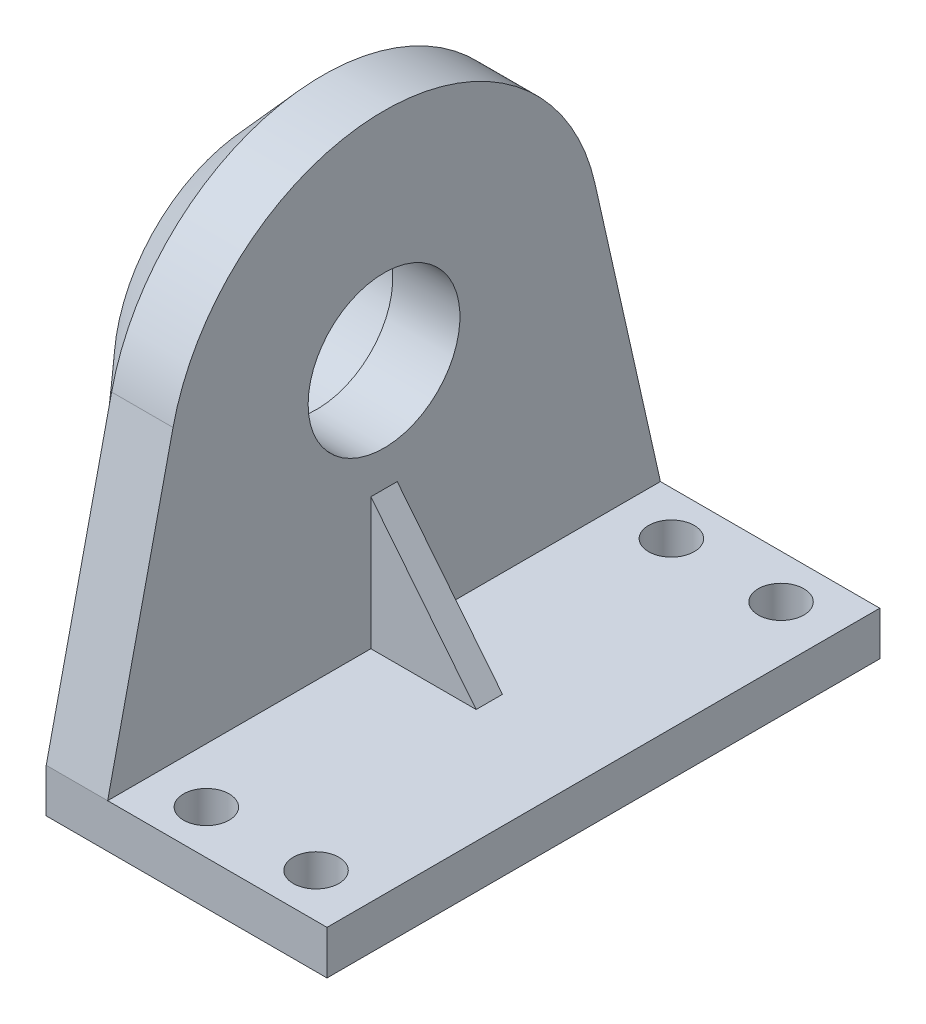
SolidWorks part; units mm, degrees
ref_plane "Front Plane" through (0, 0, 0) normal (0, 0, 1) x (1, 0, 0)
ref_plane "Top Plane" through (0, 0, 0) normal (0, 1, 0) x (1, 0, 0)
ref_plane "Right Plane" through (0, 0, 0) normal (1, 0, 0) x (0, 0, -1)
sketch "Sketch4" plane through (0, 0, 0) normal (0, 0, 1) x (1, 0, 0)
  line L0 (0, 0) -> (22.7302, 0) construction
  line L1 (0, 11.15) -> (7, 11.15)
  line L2 (0, 11.15) -> (0, 16.15)
  line L4 (7, 11.15) -> (7, 8.65)
  line L5 (7, 8.65) -> (14.6534, 8.65)
  line L6 (14.6534, 24.65) -> (14.6534, 8.65)
  line L7 (14.6534, 24.65) -> (7.6534, 24.65)
  line L8 (7.6534, 24.65) -> (0, 16.15)
  dimension "D1" = 11.15
  dimension "D2" = 7
  dimension "D3" = 2.5
  dimension "D4" = 5
  dimension "D5" = 42
  dimension "D6" = 7
  dimension "D7" = 16
revolve "Revolve1" add sketch "Sketch4" angle 360 about L0
sketch "Sketch5" plane through (14.6534, 0, 0) normal (1, 0, 0) x (0, 0, -1)
  line L0 (0, 0) -> (0, -32.7) construction
  line L3 (-31.5, -32.7) -> (31.5, -32.7)
  line L8 (-31.5, -32.7) -> (-31.5, -27.7)
  line L9 (-31.5, -27.7) -> (-24.0486, 5.4118)
  line L10 (31.5, -32.7) -> (31.5, -27.7)
  line L11 (31.5, -27.7) -> (24.0486, 5.4118)
  line L12 (31.5, -27.7) -> (-31.5, -27.7) construction
  circle A0 centre (0, 0) radius 24.65 construction
  circle A2 centre (0, 0) radius 24.65
  arc A3 (-24.0486, 5.4118) -> (24.0486, 5.4118) centre (0, 0) ccw
  dimension "D1" = 32.7
  dimension "D2" = 0
  dimension "D3" = 63
  dimension "D4" = 5
extrude "Boss-Extrude1" add sketch "Sketch5" against normal blind 7
sketch "Sketch6" plane through (14.6534, 0, 0) normal (1, 0, 0) x (0, 0, -1)
  line L0 (-31.5, -32.7) -> (31.5, -32.7) construction
  line L1 (31.5, -32.7) -> (-31.5, -32.7)
  line L2 (31.5, -32.7) -> (31.5, -27.7)
  line L3 (31.5, -27.7) -> (-31.5, -27.7)
  line L4 (-31.5, -32.7) -> (-31.5, -27.7)
extrude "Boss-Extrude2" add sketch "Sketch6" along normal blind 25
sketch "Sketch7" plane through (0, -27.7, 0) normal (0, 1, 0) x (1, 0, 0)
  line L0 (14.6534, 0) -> (39.6534, 0) construction
  line L1 (33.4034, 26.5) -> (20.9034, 26.5) construction
  line L2 (33.4034, 26.5) -> (33.4034, -26.5) construction
  line L3 (33.4034, -26.5) -> (20.9034, -26.5) construction
  line L4 (20.9034, 26.5) -> (20.9034, -26.5) construction
  line L5 (39.6534, 31.5) -> (39.6534, -31.5) construction
  line L6 (14.6534, 31.5) -> (14.6534, -31.5) construction
  line L7 (27.1534, -31.5) -> (27.1534, 31.5) construction
  line L8 (39.6534, -31.5) -> (14.6534, -31.5) construction
  line L9 (39.6534, 31.5) -> (14.6534, 31.5) construction
  line L10 (27.1534, 26.5) -> (39.6534, 26.5) construction
  circle A0 centre (20.9034, 26.5) radius 2.6
  circle A1 centre (33.4034, 26.5) radius 2.6
  circle A2 centre (33.4034, -26.5) radius 2.6
  circle A3 centre (20.9034, -26.5) radius 2.6
  point P10 (20.9034, 0)
  point P21 (27.1534, 26.5)
  point P24 (33.4034, 26.5)
  dimension "D1" = 5.2
  dimension "D2" = 5.2
  dimension "D3" = 5.2
  dimension "D4" = 5.2
  dimension "D5" = 53
extrude "Cut-Extrude1" cut sketch "Sketch7" against normal through all
sketch "Sketch8" plane through (0, 0, 0) normal (0, 0, 1) x (1, 0, 0)
  line L0 (26.6534, -27.7) -> (14.6534, -12.7)
  line L1 (39.6534, -27.7) -> (14.6534, -27.7) construction
  line L2 (14.6534, 5.4118) -> (14.6534, -27.7) construction
  line L3 (23.5034, -27.7) -> (18.3034, -27.7) construction
  line L4 (14.6534, -8.65) -> (14.6534, 8.65) construction
  line L5 (26.6534, -27.7) -> (14.6534, -27.7)
  line L6 (14.6534, -27.7) -> (14.6534, -12.7)
  dimension "D1" = 15
  dimension "D2" = 12
extrude "Boss-Extrude3" add sketch "Sketch8" along normal mid plane 3
